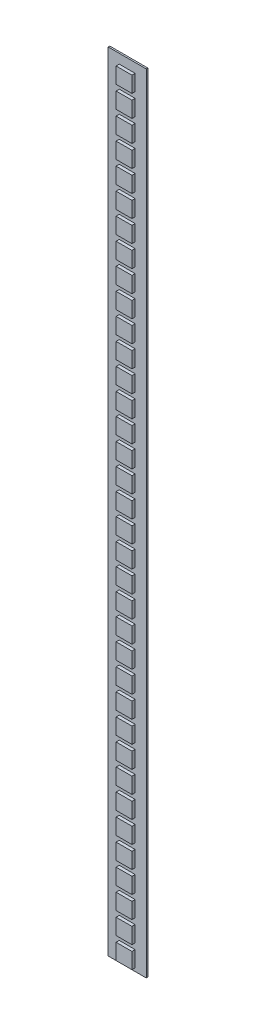
SolidWorks part; units mm, degrees
ref_plane "Front Plane" through (0, 0, 0) normal (0, 0, 1) x (1, 0, 0)
ref_plane "Top Plane" through (0, 0, 0) normal (0, 1, 0) x (1, 0, 0)
ref_plane "Right Plane" through (0, 0, 0) normal (1, 0, 0) x (0, 0, -1)
sketch "Sketch1" plane through (0, 0, 0) normal (0, 0, 1) x (1, 0, 0)
  line L0 (-6.316, 0) -> (8.0439, 0) construction
  line L1 (-6, 124) -> (6, 124)
  line L2 (-6, 124) -> (-6, -124)
  line L3 (-6, -124) -> (6, -124)
  line L4 (6, 124) -> (6, -124)
  line L5 (8.0439, 0) -> (0, 8.3609) construction
  line L6 (0, 8.3609) -> (0, -9.6962) construction
  dimension "D1" = 12
  dimension "D2" = 248
extrude "Boss-Extrude1" add sketch "Sketch1" along normal blind 0.5
sketch "Sketch2" plane through (0, 0, 0.5) normal (0, 0, 1) x (1, 0, 0)
  line L0 (0, 0) -> (0, -176.7363) construction
  line L1 (-2.5, -123) -> (2.5, -123)
  line L2 (-2.5, -123) -> (-2.5, -118)
  line L3 (-2.5, -118) -> (2.5, -118)
  line L4 (2.5, -123) -> (2.5, -118)
  line L5 (-6, -124) -> (6, -124) construction
  line L6 (-2.5, -116.17) -> (2.5, -116.17)
  line L7 (-2.5, -116.17) -> (-2.5, -111.17)
  line L8 (-2.5, -111.17) -> (2.5, -111.17)
  line L9 (2.5, -116.17) -> (2.5, -111.17)
  line L10 (0, 6.83) -> (0, -169.9063) construction
  line L11 (-2.5, -109.34) -> (2.5, -109.34)
  line L12 (-2.5, -109.34) -> (-2.5, -104.34)
  line L13 (-2.5, -104.34) -> (2.5, -104.34)
  line L14 (2.5, -109.34) -> (2.5, -104.34)
  line L15 (0, 13.66) -> (0, -163.0763) construction
  line L16 (-2.5, -102.51) -> (2.5, -102.51)
  line L17 (-2.5, -102.51) -> (-2.5, -97.51)
  line L18 (-2.5, -97.51) -> (2.5, -97.51)
  line L19 (2.5, -102.51) -> (2.5, -97.51)
  line L20 (0, 20.49) -> (0, -156.2463) construction
  line L21 (-2.5, -95.68) -> (2.5, -95.68)
  line L22 (-2.5, -95.68) -> (-2.5, -90.68)
  line L23 (-2.5, -90.68) -> (2.5, -90.68)
  line L24 (2.5, -95.68) -> (2.5, -90.68)
  line L25 (0, 27.32) -> (0, -149.4163) construction
  line L26 (-2.5, -88.85) -> (2.5, -88.85)
  line L27 (-2.5, -88.85) -> (-2.5, -83.85)
  line L28 (-2.5, -83.85) -> (2.5, -83.85)
  line L29 (2.5, -88.85) -> (2.5, -83.85)
  line L30 (0, 34.15) -> (0, -142.5863) construction
  line L31 (-2.5, -82.02) -> (2.5, -82.02)
  line L32 (-2.5, -82.02) -> (-2.5, -77.02)
  line L33 (-2.5, -77.02) -> (2.5, -77.02)
  line L34 (2.5, -82.02) -> (2.5, -77.02)
  line L35 (0, 40.98) -> (0, -135.7563) construction
  line L36 (-2.5, -75.19) -> (2.5, -75.19)
  line L37 (-2.5, -75.19) -> (-2.5, -70.19)
  line L38 (-2.5, -70.19) -> (2.5, -70.19)
  line L39 (2.5, -75.19) -> (2.5, -70.19)
  line L40 (0, 47.81) -> (0, -128.9263) construction
  line L41 (-2.5, -68.36) -> (2.5, -68.36)
  line L42 (-2.5, -68.36) -> (-2.5, -63.36)
  line L43 (-2.5, -63.36) -> (2.5, -63.36)
  line L44 (2.5, -68.36) -> (2.5, -63.36)
  line L45 (0, 54.64) -> (0, -122.0963) construction
  line L46 (-2.5, -61.53) -> (2.5, -61.53)
  line L47 (-2.5, -61.53) -> (-2.5, -56.53)
  line L48 (-2.5, -56.53) -> (2.5, -56.53)
  line L49 (2.5, -61.53) -> (2.5, -56.53)
  line L50 (0, 61.47) -> (0, -115.2663) construction
  line L51 (-2.5, -54.7) -> (2.5, -54.7)
  line L52 (-2.5, -54.7) -> (-2.5, -49.7)
  line L53 (-2.5, -49.7) -> (2.5, -49.7)
  line L54 (2.5, -54.7) -> (2.5, -49.7)
  line L55 (0, 68.3) -> (0, -108.4363) construction
  line L56 (-2.5, -47.87) -> (2.5, -47.87)
  line L57 (-2.5, -47.87) -> (-2.5, -42.87)
  line L58 (-2.5, -42.87) -> (2.5, -42.87)
  line L59 (2.5, -47.87) -> (2.5, -42.87)
  line L60 (0, 75.13) -> (0, -101.6063) construction
  line L61 (-2.5, -41.04) -> (2.5, -41.04)
  line L62 (-2.5, -41.04) -> (-2.5, -36.04)
  line L63 (-2.5, -36.04) -> (2.5, -36.04)
  line L64 (2.5, -41.04) -> (2.5, -36.04)
  line L65 (0, 81.96) -> (0, -94.7763) construction
  line L66 (-2.5, -34.21) -> (2.5, -34.21)
  line L67 (-2.5, -34.21) -> (-2.5, -29.21)
  line L68 (-2.5, -29.21) -> (2.5, -29.21)
  line L69 (2.5, -34.21) -> (2.5, -29.21)
  line L70 (0, 88.79) -> (0, -87.9463) construction
  line L71 (-2.5, -27.38) -> (2.5, -27.38)
  line L72 (-2.5, -27.38) -> (-2.5, -22.38)
  line L73 (-2.5, -22.38) -> (2.5, -22.38)
  line L74 (2.5, -27.38) -> (2.5, -22.38)
  line L75 (0, 95.62) -> (0, -81.1163) construction
  line L76 (-2.5, -20.55) -> (2.5, -20.55)
  line L77 (-2.5, -20.55) -> (-2.5, -15.55)
  line L78 (-2.5, -15.55) -> (2.5, -15.55)
  line L79 (2.5, -20.55) -> (2.5, -15.55)
  line L80 (0, 102.45) -> (0, -74.2863) construction
  line L81 (-2.5, -13.72) -> (2.5, -13.72)
  line L82 (-2.5, -13.72) -> (-2.5, -8.72)
  line L83 (-2.5, -8.72) -> (2.5, -8.72)
  line L84 (2.5, -13.72) -> (2.5, -8.72)
  line L85 (0, 109.28) -> (0, -67.4563) construction
  line L86 (-2.5, -6.89) -> (2.5, -6.89)
  line L87 (-2.5, -6.89) -> (-2.5, -1.89)
  line L88 (-2.5, -1.89) -> (2.5, -1.89)
  line L89 (2.5, -6.89) -> (2.5, -1.89)
  line L90 (0, 116.11) -> (0, -60.6263) construction
  line L91 (-2.5, -0.06) -> (2.5, -0.06)
  line L92 (-2.5, -0.06) -> (-2.5, 4.94)
  line L93 (-2.5, 4.94) -> (2.5, 4.94)
  line L94 (2.5, -0.06) -> (2.5, 4.94)
  line L95 (0, 122.94) -> (0, -53.7963) construction
  line L96 (-2.5, 6.77) -> (2.5, 6.77)
  line L97 (-2.5, 6.77) -> (-2.5, 11.77)
  line L98 (-2.5, 11.77) -> (2.5, 11.77)
  line L99 (2.5, 6.77) -> (2.5, 11.77)
  line L100 (0, 129.77) -> (0, -46.9663) construction
  line L101 (-2.5, 13.6) -> (2.5, 13.6)
  line L102 (-2.5, 13.6) -> (-2.5, 18.6)
  line L103 (-2.5, 18.6) -> (2.5, 18.6)
  line L104 (2.5, 13.6) -> (2.5, 18.6)
  line L105 (0, 136.6) -> (0, -40.1363) construction
  line L106 (-2.5, 20.43) -> (2.5, 20.43)
  line L107 (-2.5, 20.43) -> (-2.5, 25.43)
  line L108 (-2.5, 25.43) -> (2.5, 25.43)
  line L109 (2.5, 20.43) -> (2.5, 25.43)
  line L110 (0, 143.43) -> (0, -33.3063) construction
  line L111 (-2.5, 27.26) -> (2.5, 27.26)
  line L112 (-2.5, 27.26) -> (-2.5, 32.26)
  line L113 (-2.5, 32.26) -> (2.5, 32.26)
  line L114 (2.5, 27.26) -> (2.5, 32.26)
  line L115 (0, 150.26) -> (0, -26.4763) construction
  line L116 (-2.5, 34.09) -> (2.5, 34.09)
  line L117 (-2.5, 34.09) -> (-2.5, 39.09)
  line L118 (-2.5, 39.09) -> (2.5, 39.09)
  line L119 (2.5, 34.09) -> (2.5, 39.09)
  line L120 (0, 157.09) -> (0, -19.6463) construction
  line L121 (-2.5, 40.92) -> (2.5, 40.92)
  line L122 (-2.5, 40.92) -> (-2.5, 45.92)
  line L123 (-2.5, 45.92) -> (2.5, 45.92)
  line L124 (2.5, 40.92) -> (2.5, 45.92)
  line L125 (0, 163.92) -> (0, -12.8163) construction
  line L126 (-2.5, 47.75) -> (2.5, 47.75)
  line L127 (-2.5, 47.75) -> (-2.5, 52.75)
  line L128 (-2.5, 52.75) -> (2.5, 52.75)
  line L129 (2.5, 47.75) -> (2.5, 52.75)
  line L130 (0, 170.75) -> (0, -5.9863) construction
  line L131 (-2.5, 54.58) -> (2.5, 54.58)
  line L132 (-2.5, 54.58) -> (-2.5, 59.58)
  line L133 (-2.5, 59.58) -> (2.5, 59.58)
  line L134 (2.5, 54.58) -> (2.5, 59.58)
  line L135 (0, 177.58) -> (0, 0.8437) construction
  line L136 (-2.5, 61.41) -> (2.5, 61.41)
  line L137 (-2.5, 61.41) -> (-2.5, 66.41)
  line L138 (-2.5, 66.41) -> (2.5, 66.41)
  line L139 (2.5, 61.41) -> (2.5, 66.41)
  line L140 (0, 184.41) -> (0, 7.6737) construction
  line L141 (-2.5, 68.24) -> (2.5, 68.24)
  line L142 (-2.5, 68.24) -> (-2.5, 73.24)
  line L143 (-2.5, 73.24) -> (2.5, 73.24)
  line L144 (2.5, 68.24) -> (2.5, 73.24)
  line L145 (0, 191.24) -> (0, 14.5037) construction
  line L146 (-2.5, 75.07) -> (2.5, 75.07)
  line L147 (-2.5, 75.07) -> (-2.5, 80.07)
  line L148 (-2.5, 80.07) -> (2.5, 80.07)
  line L149 (2.5, 75.07) -> (2.5, 80.07)
  line L150 (0, 198.07) -> (0, 21.3337) construction
  line L151 (-2.5, 81.9) -> (2.5, 81.9)
  line L152 (-2.5, 81.9) -> (-2.5, 86.9)
  line L153 (-2.5, 86.9) -> (2.5, 86.9)
  line L154 (2.5, 81.9) -> (2.5, 86.9)
  line L155 (0, 204.9) -> (0, 28.1637) construction
  line L156 (-2.5, 88.73) -> (2.5, 88.73)
  line L157 (-2.5, 88.73) -> (-2.5, 93.73)
  line L158 (-2.5, 93.73) -> (2.5, 93.73)
  line L159 (2.5, 88.73) -> (2.5, 93.73)
  line L160 (0, 211.73) -> (0, 34.9937) construction
  line L161 (-2.5, 95.56) -> (2.5, 95.56)
  line L162 (-2.5, 95.56) -> (-2.5, 100.56)
  line L163 (-2.5, 100.56) -> (2.5, 100.56)
  line L164 (2.5, 95.56) -> (2.5, 100.56)
  line L165 (0, 218.56) -> (0, 41.8237) construction
  line L166 (-2.5, 102.39) -> (2.5, 102.39)
  line L167 (-2.5, 102.39) -> (-2.5, 107.39)
  line L168 (-2.5, 107.39) -> (2.5, 107.39)
  line L169 (2.5, 102.39) -> (2.5, 107.39)
  line L170 (0, 225.39) -> (0, 48.6537) construction
  line L171 (-2.5, 109.22) -> (2.5, 109.22)
  line L172 (-2.5, 109.22) -> (-2.5, 114.22)
  line L173 (-2.5, 114.22) -> (2.5, 114.22)
  line L174 (2.5, 109.22) -> (2.5, 114.22)
  line L175 (0, 232.22) -> (0, 55.4837) construction
  line L176 (-2.5, 116.05) -> (2.5, 116.05)
  line L177 (-2.5, 116.05) -> (-2.5, 121.05)
  line L178 (-2.5, 121.05) -> (2.5, 121.05)
  line L179 (2.5, 116.05) -> (2.5, 121.05)
  line L180 (0, 239.05) -> (0, 62.3137) construction
  dimension "D1" = 5
  dimension "D2" = 1
  dimension "D3" = 36
extrude "Boss-Extrude2" add sketch "Sketch2" along normal blind 1
sketch "Sketch3" plane through (0, 124, 0) normal (0, 1, 0) x (1, 0, 0)
  line L0 (0, 2.3076) -> (0, -7.0222) construction
